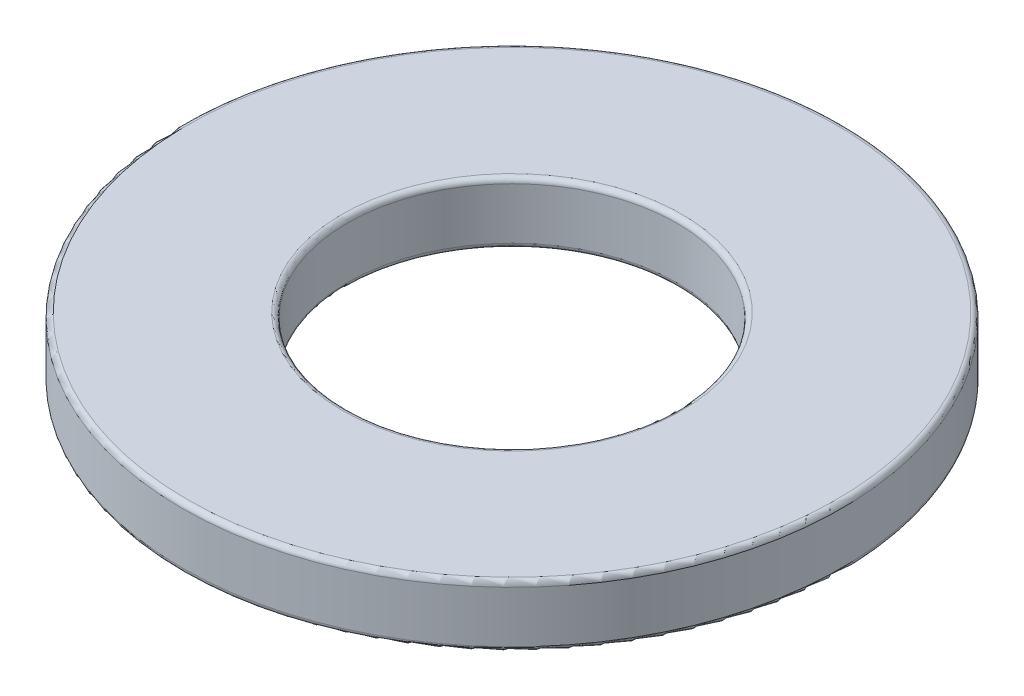
SolidWorks part; units mm, degrees
material "NdFeB"
ref_plane "Front Plane" through (0, 0, 0) normal (0, 0, 1) x (1, 0, 0)
ref_plane "Top Plane" through (0, 0, 0) normal (0, 1, 0) x (1, 0, 0)
ref_plane "Right Plane" through (0, 0, 0) normal (1, 0, 0) x (0, 0, -1)
sketch "Sketch1" plane through (0, 0, 0) normal (1, 0, 0) x (0, 0, -1)
  line L0 (0, 17.9076) -> (0, -14.7689) construction
  line L1 (-16, 1.25) -> (-16, -1.25)
  line L2 (-15.75, -1.5) -> (-8.25, -1.5)
  line L3 (-8, -1.25) -> (-8, 1.25)
  line L4 (-15.75, 1.5) -> (-8.25, 1.5)
  arc A0 (-8.25, 1.5) -> (-8, 1.25) centre (-8.25, 1.25) cw
  arc A1 (-8, -1.25) -> (-8.25, -1.5) centre (-8.25, -1.25) cw
  arc A2 (-16, -1.25) -> (-15.75, -1.5) centre (-15.75, -1.25) ccw
  arc A3 (-16, 1.25) -> (-15.75, 1.5) centre (-15.75, 1.25) cw
  point P7 (-8, 0)
  dimension "D4" = 0.25
  dimension "D1" = 32
  dimension "D2" = 3
  dimension "D3" = 16
revolve "Revolve1" add sketch "Sketch1" angle 360 about L0
